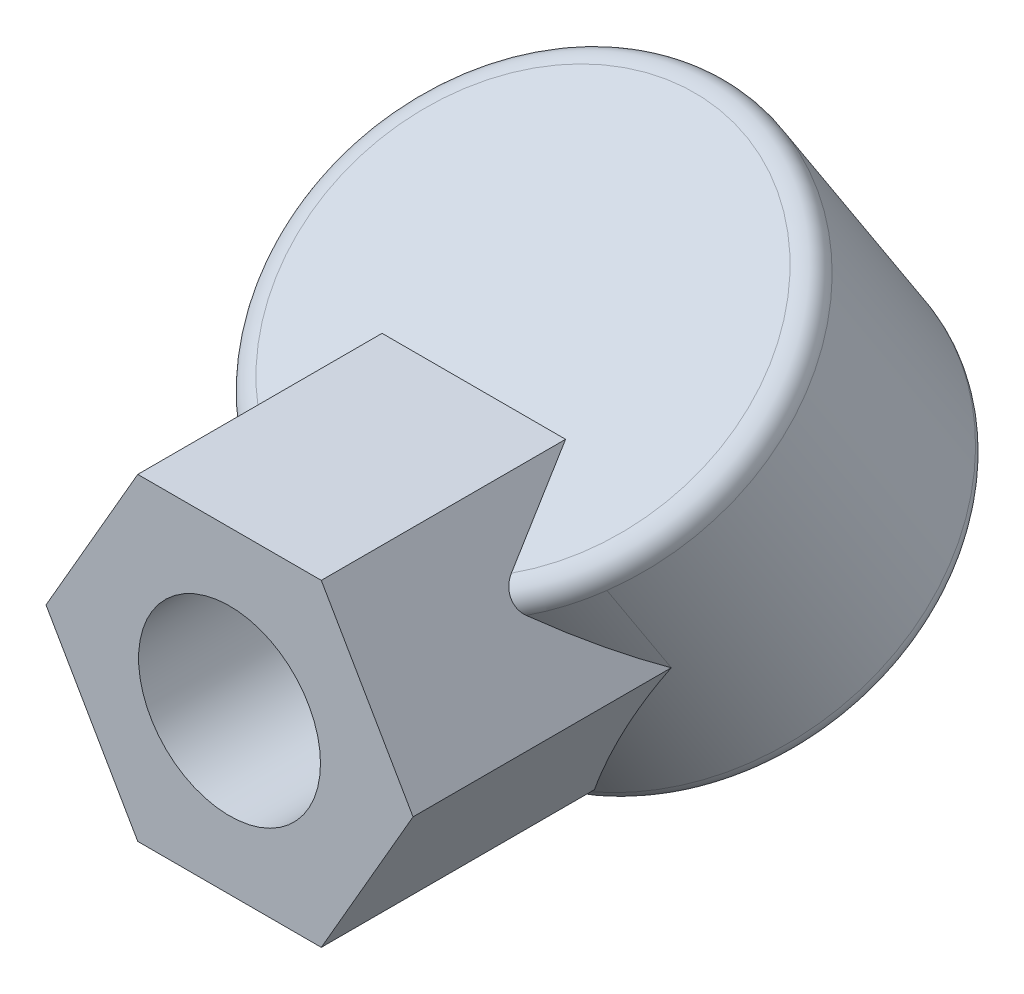
SolidWorks part; units mm, degrees
ref_plane "Płaszczyzna przednia" through (0, 0, 0) normal (0, 0, 1) x (1, 0, 0)
ref_plane "Płaszczyzna górna" through (0, 0, 0) normal (0, 1, 0) x (1, 0, 0)
ref_plane "Płaszczyzna prawa" through (0, 0, 0) normal (1, 0, 0) x (0, 0, -1)
sketch "Szkic3" plane through (0, 0, 0) normal (1, 0, 0) x (0, 0, -1)
  line L2 (0, 0) -> (-36.5355, 0) construction
  line L3 (0, 0) -> (-14.1606, 21.8054) construction
  line L4 (0, 0) -> (-28.2259, -18.3301) construction
  line L5 (-7.0803, 10.9027) -> (-15.467, 5.4563)
  line L6 (-15.467, 5.4563) -> (-8.3867, -5.4464)
  line L8 (-3.8125, 5.8707) -> (-7.0803, 10.9027)
  line L9 (-8.3867, -5.4464) -> (-1.3867, -6.8613)
  arc A2 (-3.8125, 5.8707) -> (-1.3867, -6.8613) centre (0, 0) ccw
  dimension "D1" = 14
  dimension "D2" = 33
  dimension "D3" = 10
  dimension "D4" = 13
  dimension "D5" = 7
revolve "Obrót1" add sketch "Szkic3" angle 360 about L8
sketch "Szkic4" plane through (0, 0, 0) normal (0, 0, 1) x (1, 0, 0)
  line L1 (-8.1132, 4.4169) -> (-7.8818, -4.8178)
  line L2 (-7.8818, -4.8178) -> (0.2314, -9.2347)
  line L3 (0.2314, -9.2347) -> (8.1132, -4.4169)
  line L4 (8.1132, -4.4169) -> (7.8818, 4.8178)
  line L5 (7.8818, 4.8178) -> (-0.2314, 9.2347)
  line L6 (-0.2314, 9.2347) -> (-8.1132, 4.4169)
  circle A0 centre (0, 0) radius 8 construction
  dimension "D1" = 16
ref_plane "Płaszczyzna1" through (0, 0, 20) normal (0, 0, 1) x (1, 0, 0)
sketch "Szkic5" plane through (0, 0, 20) normal (0, 0, 1) x (1, 0, 0)
  line L1 (8.0829, 2.5) -> (4.0473, 9.4899)
  line L2 (4.0473, 9.4899) -> (-4.024, 9.4899)
  line L3 (-4.024, 9.4899) -> (-8.0597, 2.5)
  line L4 (-8.0597, 2.5) -> (-4.024, -4.4899)
  line L5 (-4.024, -4.4899) -> (4.0473, -4.4899)
  line L6 (4.0473, -4.4899) -> (8.0829, 2.5)
  line L7 (0.0116, 2.5) -> (16.5506, 2.5) construction
  circle A0 centre (0.0116, 2.5) radius 6.9899 construction
  circle A1 centre (0.0116, 2.5) radius 4
  dimension "D1" = 8
  dimension "D2" = 13.9799
  dimension "D3" = 2.5
extrude "Dodanie-wyciągnięcie2" add sketch "Szkic5" against normal up to next
fillet "Zaokrąglenie1" radius 1 2 edges at (0, 5.4464, -8.3867) (-0.0116, 16.3491, -1.3064)
